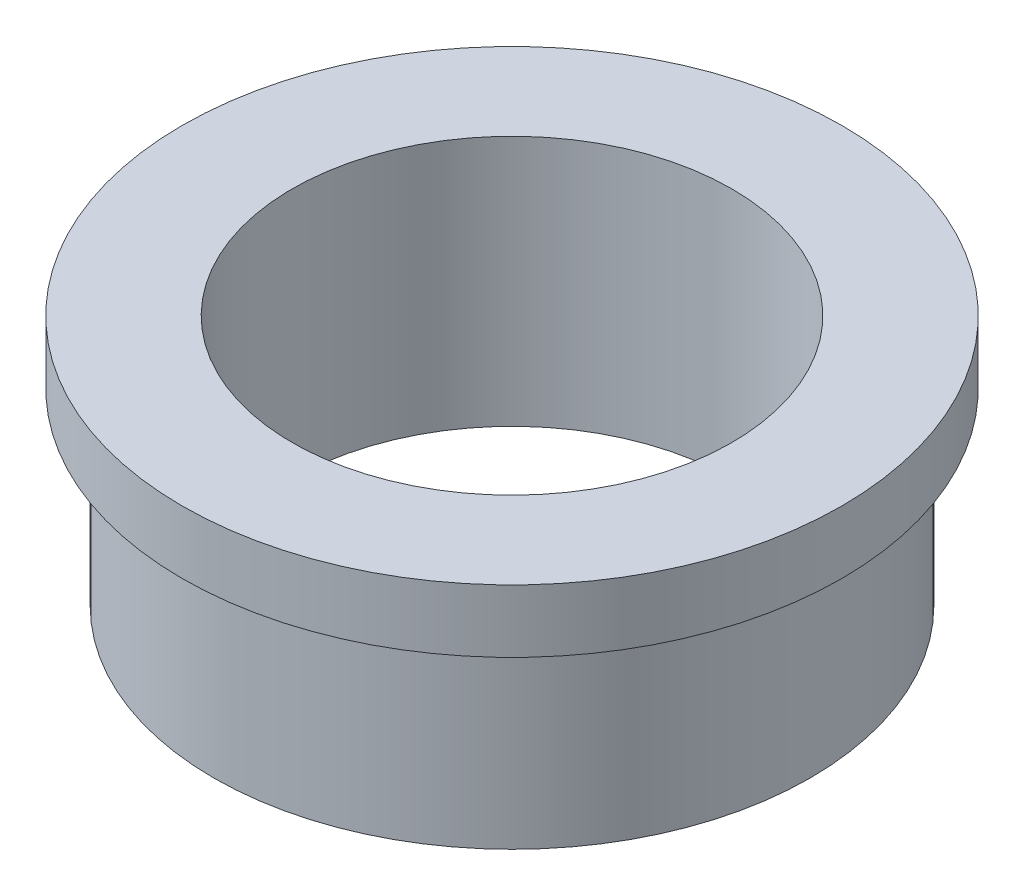
SolidWorks part; units mm, degrees
ref_plane "Front Plane" through (0, 0, 0) normal (0, 0, 1) x (1, 0, 0)
ref_plane "Top Plane" through (0, 0, 0) normal (0, 1, 0) x (1, 0, 0)
ref_plane "Right Plane" through (0, 0, 0) normal (1, 0, 0) x (0, 0, -1)
sketch "Sketch1" plane through (0, 0, 0) normal (0, 0, 1) x (1, 0, 0)
  line L0 (-7, 0) -> (-9.5, 0)
  line L1 (-7, 0) -> (-7, 8)
  line L2 (-7, 8) -> (-10.5, 8)
  line L3 (-10.5, 8) -> (-10.5, 6)
  line L4 (-10.5, 6) -> (-9.5, 6)
  line L5 (-9.5, 6) -> (-9.5, 0)
  line L6 (0, 0) -> (0, 23.0008) construction
  dimension "D1" = 7
  dimension "D2" = 2.5
  dimension "D3" = 8
  dimension "D4" = 3.5
  dimension "D5" = 2
revolve "Revolve1" add sketch "Sketch1" angle 360 about L6
